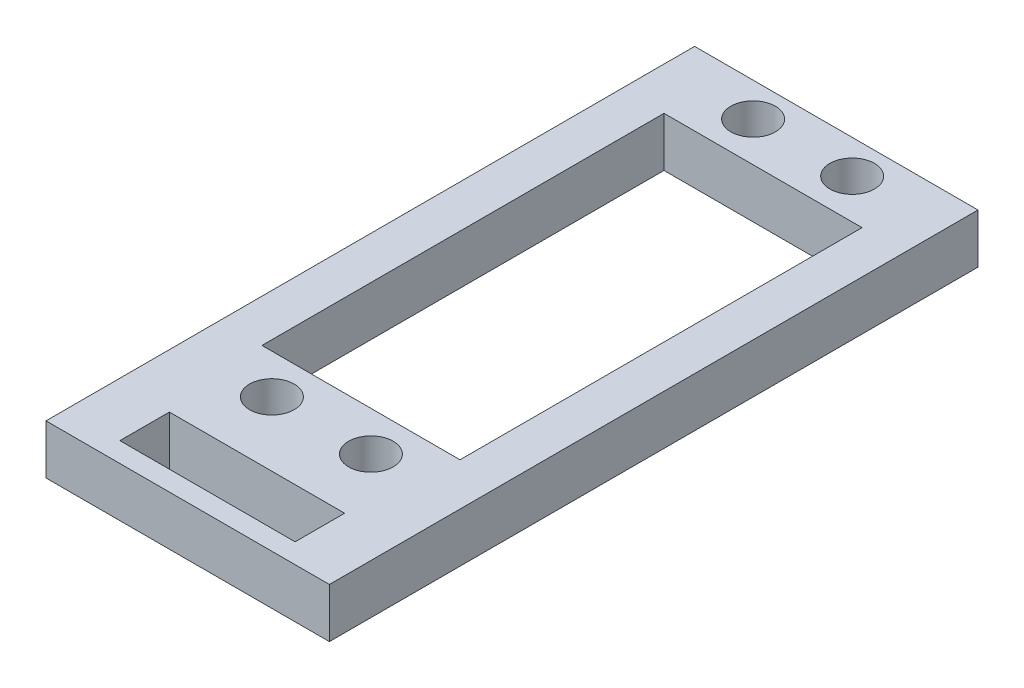
SolidWorks part; units mm, degrees
ref_plane "Front Plane" through (0, 0, 0) normal (0, 0, 1) x (1, 0, 0)
ref_plane "Top Plane" through (0, 0, 0) normal (0, 1, 0) x (1, 0, 0)
ref_plane "Right Plane" through (0, 0, 0) normal (1, 0, 0) x (0, 0, -1)
sketch "Sketch1" plane through (0, 0, 0) normal (0, 1, 0) x (1, 0, 0)
  line L0 (0, 0) -> (20, -40.6) construction
  line L1 (0, 0) -> (20, 0)
  line L2 (0, 0) -> (0, -40.6)
  line L3 (0, -40.6) -> (20, -40.6)
  line L4 (20, 0) -> (20, -40.6)
  line L5 (20, -40.6) -> (20.2313, -40.5167) construction
  line L6 (0, -40.6) -> (20, 0) construction
  line L7 (24.3089, -20.3) -> (-4.3089, -20.3) construction
  line L8 (-4.3089, -48) -> (24.3089, -48) construction
  line L9 (-4.3089, -48) -> (-4.3089, 7.4)
  line L10 (-4.3089, 7.4) -> (24.3089, 7.4)
  line L11 (24.3089, -48) -> (24.3089, 7.4)
  line L12 (-4.3089, -48) -> (24.3089, 7.4) construction
  line L13 (-4.3089, 7.4) -> (24.3089, -48) construction
  line L14 (-4.3089, -48) -> (24.3089, -48) construction
  line L15 (-4.3089, -48) -> (-4.3089, -58.1)
  line L16 (-4.3089, -58.1) -> (24.3089, -58.1)
  line L17 (24.3089, -48) -> (24.3089, -58.1)
  line L18 (19.5983, -48) -> (0.4017, -48) construction
  line L20 (1.1519, -56.1) -> (18.8481, -56.1)
  line L21 (1.1519, -56.1) -> (1.1519, -51.1)
  line L22 (10, 7.4) -> (10, -48) construction
  line L23 (1.1519, -51.1) -> (18.8481, -51.1)
  line L24 (18.8481, -56.1) -> (18.8481, -51.1)
  line L25 (1.1519, -56.1) -> (18.8481, -51.1) construction
  line L26 (1.1519, -51.1) -> (18.8481, -56.1) construction
  circle A0 centre (5, 4) radius 2.25
  circle A1 centre (15, 4) radius 2.25
  circle A2 centre (5, -44.6) radius 2.25
  circle A3 centre (15, -44.6) radius 2.25
  point P4 (10, -20.3)
  point P14 (10, -53.6)
  point P32 (0, 0)
  dimension "D6" = 4.5
  dimension "D1" = 40.6
  dimension "D2" = 20
  dimension "D3" = 55.4
  dimension "D4" = 5
  dimension "D5" = 65.5
  dimension "D7" = 10
  dimension "D8" = 48.6
  dimension "D9" = 2
extrude "Boss-Extrude1" add sketch "Sketch1" along normal blind 5
